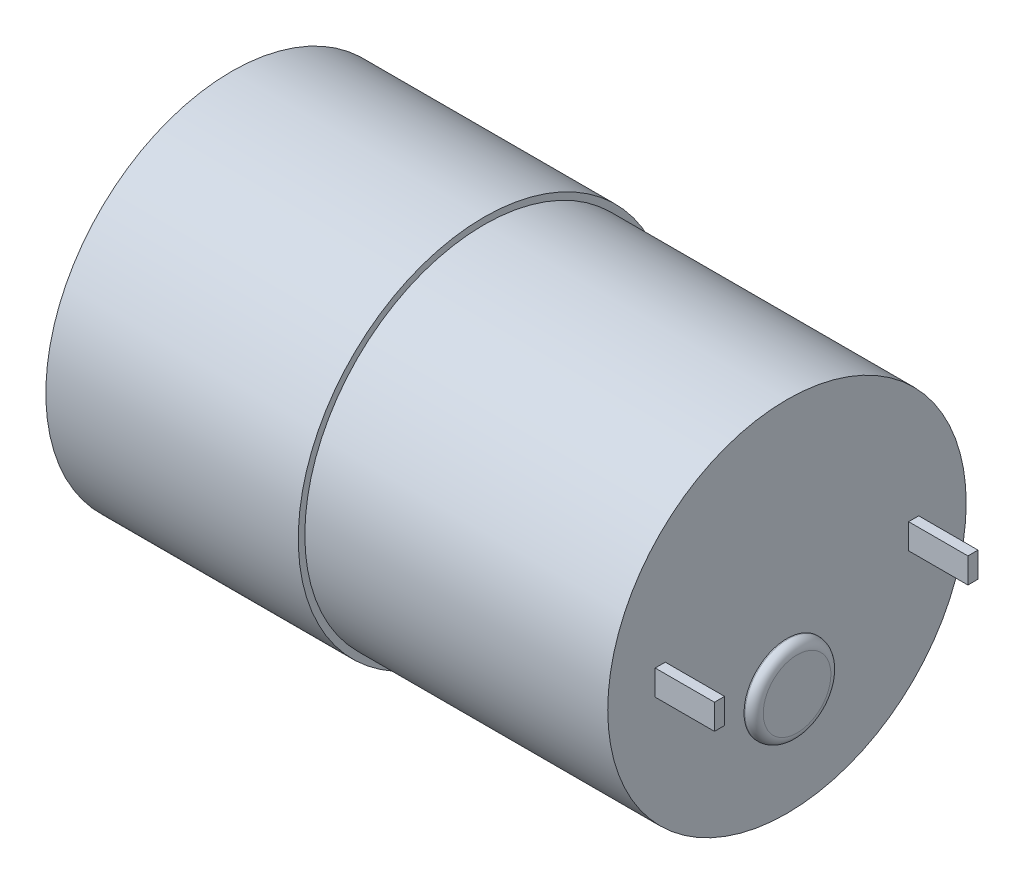
SolidWorks part; units mm, degrees
ref_plane "Front Plane" through (0, 0, 0) normal (0, 0, 1) x (1, 0, 0)
ref_plane "Top Plane" through (0, 0, 0) normal (0, 1, 0) x (1, 0, 0)
ref_plane "Right Plane" through (0, 0, 0) normal (1, 0, 0) x (0, 0, -1)
sketch "Sketch1" plane through (0, 0, 0) normal (0, 0, 1) x (1, 0, 0)
  line L2 (30, 0) -> (30, 17.75)
  line L3 (30, 17.75) -> (0, 17.75)
  line L4 (0, 17.75) -> (0, 18.4)
  line L5 (0, 18.4) -> (-25, 18.4)
  line L6 (-25, 18.4) -> (-25, 0)
  line L11 (-25, 0) -> (30, 0)
  dimension "D1" = 0.65
  dimension "D2" = 30
  dimension "D3" = 18.4
  dimension "D4" = 25
revolve "Revolve1" add sketch "Sketch1" angle 360 about L11
sketch "Sketch2" plane through (30, 0, 0) normal (1, 0, 0) x (0, 0, -1)
  circle A0 centre (0, -7) radius 4.25
  dimension "D1" = 7
  dimension "D2" = 8.5
extrude "Boss-Extrude1" add sketch "Sketch2" along normal blind 1
fillet "Fillet1" radius 0.9 1 edges at (31, -2.75, 0)
ref_axis "Axis1" through (30.1, -7, 0) along (-1, 0, 0)
sketch "Sketch4" plane through (0, 0, 0) normal (0, 0, 1) x (1, 0, 0)
  line L0 (30.1, -7) -> (30, -7) construction
  line L1 (-20.0341, -7) -> (-26.5, -7)
  line L2 (-20.0341, -7) -> (-25, -1)
  line L3 (-25, 18.4) -> (-25, -18.4) construction
  line L4 (-25, -1) -> (-31.5, -1)
  line L5 (-31.5, -1) -> (-31.5, -4)
  line L6 (-31.5, -4) -> (-26.5, -4)
  line L7 (-26.5, -4) -> (-26.5, -7)
  dimension "D1" = 6
  dimension "D2" = 6.5
  dimension "D3" = 5
  dimension "D4" = 3
revolve "Revolve2" add sketch "Sketch4" angle 360 about axis through (30.1, -7, 0) along (-1, 0, 0)
chamfer "Chamfer1" distance 1.65 angle 45 1 edges at (-31.5, -7, -6)
sketch "Sketch7" plane through (-25, 0, 0) normal (-1, 0, 0) x (0, 0, 1)
  line L0 (-9.6852, -7) -> (-8.58, -7) construction
  line L1 (8.58, -7) -> (9.6852, -7) construction
  line L2 (-8.7, -7) -> (-8.7, -7.4) construction
  line L3 (8.7, -7) -> (8.7, -7.4) construction
  arc A0 (-9.6852, -7) -> (9.6852, -7) centre (0, 0) cw
  circle A1 centre (0, 0) radius 18.4 construction
  arc A2 (-8.58, -7) -> (8.58, -7) centre (0, -7) cw
  circle A3 centre (0, -7) radius 6 construction
  circle A4 centre (-15.5, 0) radius 1
  circle A5 centre (-7.75, 13.4234) radius 1
  circle A6 centre (15.5, 0) radius 1
  circle A7 centre (7.75, 13.4234) radius 1
  circle A8 centre (-7.75, -13.4234) radius 1
  circle A9 centre (7.75, -13.4234) radius 1
  circle A10 centre (0, 15.5) radius 1
  circle A11 centre (13.4234, -7.75) radius 1
  circle A12 centre (-13.4234, -7.75) radius 1
  spline S0 degree 2 poles (-9.6852, -7) (-8.6593, -7.9878) (-8.58, -7) knots 0 0 0 1 1 1
  spline S1 degree 2 poles (8.58, -7) (8.6593, -7.9878) (9.6852, -7) knots 0 0 0 1 1 1
  point P32 (0, 0)
  point P40 (0, 0)
  dimension "D1" = 6.45
  dimension "D2" = 2.58
  dimension "D10" = 2
  dimension "D11" = 15.5
  dimension "D12" = 2
  dimension "D14" = 15.5
  dimension "D16" = 3
  dimension "D17" = 2
  dimension "D19" = 0
  dimension "D18" = 15.5
  dimension "D3" = 7
  dimension "D4" = 0.4
  dimension "D5" = 0
  dimension "D6" = 0.12
  dimension "D7" = 0.4
  dimension "D8" = 0.12
  dimension "D9" = 0
  dimension "D13" = 15.5
  dimension "D15" = 0
  dimension "D20" = 3
hole_wizard "M3x0.5 Tapped Hole2" positions "3DSketch4" profile "Sketch11" tap size "M3x0.5" standard "ANSI Metric"
sketch3d "3DSketch4"
  point P0 (-25, 0, -15.5)
  point P3 (-25, 13.4234, -7.75)
  point P6 (-25, 15.5, 0)
  point P9 (-25, 13.4234, 7.75)
  point P12 (-25, 0, 15.5)
  point P15 (-25, -7.75, 13.4234)
  point P18 (-25, -13.4234, 7.75)
  point P21 (-25, -13.4234, -7.75)
  point P24 (-25, -7.75, -13.4234)
cosmetic thread "Hole Thread10" parameters "D1"=0.9, "D2"=3
cosmetic thread "Hole Thread11" parameters "D1"=0.9, "D2"=3
cosmetic thread "Hole Thread12" parameters "D1"=0.9, "D2"=3
cosmetic thread "Hole Thread13" parameters "D1"=0.9, "D2"=3
cosmetic thread "Hole Thread14" parameters "D1"=0.9, "D2"=3
cosmetic thread "Hole Thread15" parameters "D1"=0.9, "D2"=3
cosmetic thread "Hole Thread16" parameters "D1"=0.9, "D2"=3
cosmetic thread "Hole Thread17" parameters "D1"=0.9, "D2"=3
cosmetic thread "Hole Thread18" parameters "D1"=0.9, "D2"=3
sketch "Sketch11" plane through (-25, 0, -15.5) normal (0, 1, 0) x (0, 0, 1)
  line L0 (0, 0) -> (0, 1.7511)
  line L1 (0, 1.7511) -> (1.25, 1)
  line L2 (1.25, 1) -> (1.25, 0)
  line L5 (1.25, 0) -> (0, 0)
  line L10 (0, 1.7511) -> (-1.25, 1) construction
  line L11 (0, -6.35) -> (0, 107.95) construction
  dimension "Tap Drill Dia." = 2.5
  dimension "Tap Drill Depth" = 1
  dimension "Drill Angle" = 118
extrude "Cut-Extrude3" cut sketch "Sketch7" against normal blind 1 contours A0 S1 A2 S0
sketch "Sketch12" plane through (30, 0, 0) normal (1, 0, 0) x (0, 0, -1)
  line L1 (12.05, 1.25) -> (13.05, 1.25)
  line L2 (12.05, 1.25) -> (12.05, -1.25)
  line L3 (12.05, -1.25) -> (13.05, -1.25)
  line L4 (13.05, 1.25) -> (13.05, -1.25)
  line L5 (-13.05, 1.25) -> (-12.05, 1.25)
  line L6 (-13.05, 1.25) -> (-13.05, -1.25)
  line L7 (-13.05, -1.25) -> (-12.05, -1.25)
  line L8 (-12.05, 1.25) -> (-12.05, -1.25)
  dimension "D1" = 1
  dimension "D2" = 1
  dimension "D3" = 12.05
  dimension "D4" = 12.05
  dimension "D5" = 2.5
  dimension "D6" = 2.5
  dimension "D7" = 1.25
  dimension "D8" = 1.25
extrude "Boss-Extrude3" add sketch "Sketch12" along normal blind 5.87
